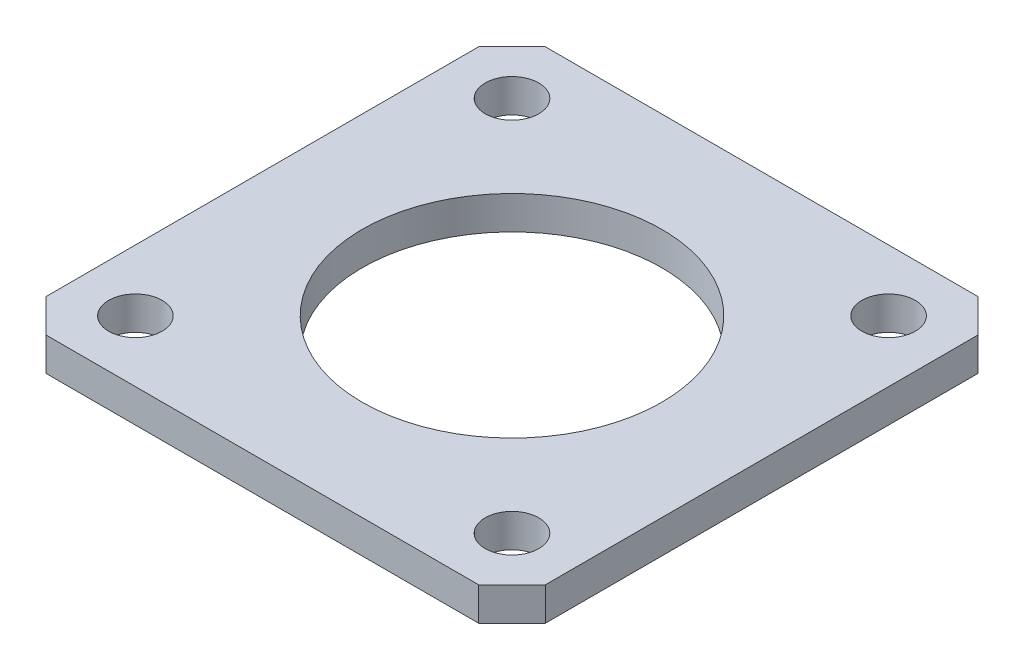
SolidWorks part; units mm, degrees
ref_plane "Front Plane" through (0, 0, 0) normal (0, 0, 1) x (1, 0, 0)
ref_plane "Top Plane" through (0, 0, 0) normal (0, 1, 0) x (1, 0, 0)
ref_plane "Right Plane" through (0, 0, 0) normal (1, 0, 0) x (0, 0, -1)
ref_plane "Plane4" through (0, 0, 0) normal (0, -1, 0) x (1, 0, 0)
sketch "Sketch1" plane through (0, 0, 0) normal (0, -1, 0) x (1, 0, 0)
  line L0 (47.625, -44.45) -> (47.625, -3.175)
  line L1 (47.625, -3.175) -> (44.45, 0)
  line L2 (44.45, 0) -> (3.175, 0)
  line L3 (3.175, 0) -> (0, -3.175)
  line L4 (0, -3.175) -> (0, -44.45)
  line L5 (0, -44.45) -> (3.175, -47.625)
  line L6 (3.175, -47.625) -> (44.45, -47.625)
  line L7 (44.45, -47.625) -> (47.625, -44.45)
  circle A0 centre (5.852, -5.852) radius 2.5527
  circle A1 centre (41.773, -41.773) radius 2.5527
  circle A2 centre (23.8125, -23.8125) radius 14.2875
  circle A3 centre (5.852, -41.773) radius 2.5527
  circle A4 centre (41.773, -5.852) radius 2.5527
  point P18 (0, -23.8125)
  dimension "D3" = 35.921
  dimension "D4" = 35.921
  dimension "D5" = 28.575
  dimension "D6" = 23.8125
  dimension "D7" = 23.8125
  dimension "D1" = 41.275
  dimension "D2" = 47.625
extrude "Boss-Extrude1" add sketch "Sketch1" against normal blind 3.175
